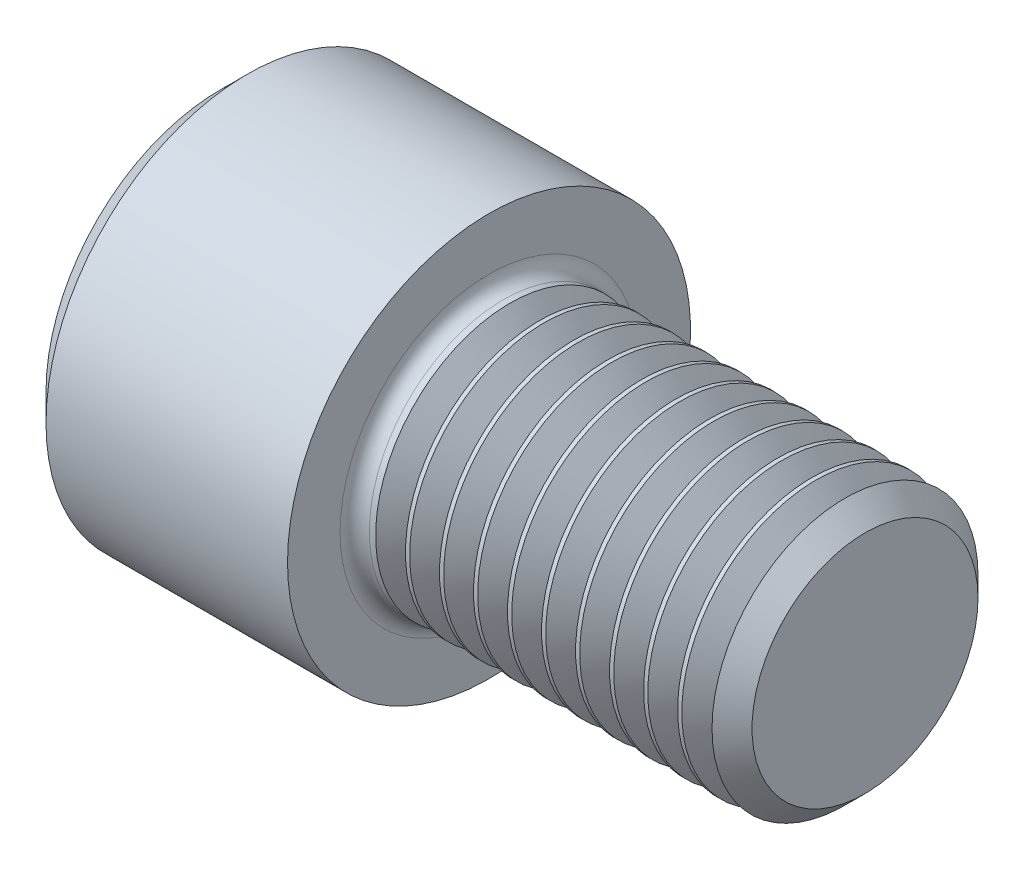
SolidWorks part; units mm, degrees
material "AISI 4130 Steel, normalized at 870C"
ref_plane "Front Plane" through (0, 0, 0) normal (0, 0, 1) x (1, 0, 0)
ref_plane "Top Plane" through (0, 0, 0) normal (0, 1, 0) x (1, 0, 0)
ref_plane "Right Plane" through (0, 0, 0) normal (1, 0, 0) x (0, 0, -1)
ref_plane "Plane1" through (0, 0, 0) normal (0, 0, -1) x (-1, 0, 0)
sketch "Sketch1" plane through (0, 0, 0) normal (0, 0, -1) x (-1, 0, 0)
  line L0 (-7.9375, 5.9538) -> (-7.9375, 0)
  line L1 (-7.9375, 0) -> (0, 0)
  line L2 (0, 0) -> (0, 5.9538)
  line L3 (0, 5.9538) -> (-7.9375, 5.9538)
  line L4 (-7.9375, 0) -> (0, 0) construction
revolve "Revolve1" add sketch "Sketch1" angle 360 about L4
sketch "Sketch2" plane through (7.9375, 0, 0) normal (1, 0, 0) x (0, 0, -1)
  circle A0 centre (0, 0) radius 3.9687
extrude "Boss-Extrude1" add sketch "Sketch2" along normal blind 0.6181
sketch "Sketch3" plane through (8.5556, 0, 0) normal (1, 0, 0) x (0, 0, -1)
  circle A0 centre (0, 0) radius 3.9687
extrude "Boss-Extrude2" add sketch "Sketch3" along normal blind 0.4411 draft 55
sketch "Sketch4" plane through (8.9967, 0, 0) normal (1, 0, 0) x (0, 0, -1)
  circle A0 centre (0, 0) radius 3.3388
extrude "Boss-Extrude3" add sketch "Sketch4" along normal blind 0.4411 draft 55 draft outward yes
sketch "Sketch5" plane through (9.4378, 0, 0) normal (1, 0, 0) x (0, 0, -1)
  circle A0 centre (0, 0) radius 3.9687
extrude "Boss-Extrude4" add sketch "Sketch5" along normal blind 0.1232
sketch "Sketch6" plane through (9.5609, 0, 0) normal (1, 0, 0) x (0, 0, -1)
  circle A0 centre (0, 0) radius 3.9687
extrude "Boss-Extrude5" add sketch "Sketch6" along normal blind 0.4411 draft 55
sketch "Sketch7" plane through (10.002, 0, 0) normal (1, 0, 0) x (0, 0, -1)
  circle A0 centre (0, 0) radius 3.3388
extrude "Boss-Extrude6" add sketch "Sketch7" along normal blind 0.4411 draft 55 draft outward yes
sketch "Sketch8" plane through (10.4431, 0, 0) normal (1, 0, 0) x (0, 0, -1)
  circle A0 centre (0, 0) radius 3.9687
extrude "Boss-Extrude7" add sketch "Sketch8" along normal blind 0.1232
sketch "Sketch9" plane through (10.5663, 0, 0) normal (1, 0, 0) x (0, 0, -1)
  circle A0 centre (0, 0) radius 3.9687
extrude "Boss-Extrude8" add sketch "Sketch9" along normal blind 0.4411 draft 55
sketch "Sketch10" plane through (11.0073, 0, 0) normal (1, 0, 0) x (0, 0, -1)
  circle A0 centre (0, 0) radius 3.3388
extrude "Boss-Extrude9" add sketch "Sketch10" along normal blind 0.4411 draft 55 draft outward yes
sketch "Sketch11" plane through (11.4484, 0, 0) normal (1, 0, 0) x (0, 0, -1)
  circle A0 centre (0, 0) radius 3.9687
extrude "Boss-Extrude10" add sketch "Sketch11" along normal blind 0.1232
sketch "Sketch12" plane through (11.5716, 0, 0) normal (1, 0, 0) x (0, 0, -1)
  circle A0 centre (0, 0) radius 3.9687
extrude "Boss-Extrude11" add sketch "Sketch12" along normal blind 0.4411 draft 55
sketch "Sketch13" plane through (12.0127, 0, 0) normal (1, 0, 0) x (0, 0, -1)
  circle A0 centre (0, 0) radius 3.3388
extrude "Boss-Extrude12" add sketch "Sketch13" along normal blind 0.4411 draft 55 draft outward yes
sketch "Sketch14" plane through (12.4538, 0, 0) normal (1, 0, 0) x (0, 0, -1)
  circle A0 centre (0, 0) radius 3.9687
extrude "Boss-Extrude13" add sketch "Sketch14" along normal blind 0.1232
sketch "Sketch15" plane through (12.5769, 0, 0) normal (1, 0, 0) x (0, 0, -1)
  circle A0 centre (0, 0) radius 3.9688
extrude "Boss-Extrude14" add sketch "Sketch15" along normal blind 0.4411 draft 55
sketch "Sketch16" plane through (13.018, 0, 0) normal (1, 0, 0) x (0, 0, -1)
  circle A0 centre (0, 0) radius 3.3388
extrude "Boss-Extrude15" add sketch "Sketch16" along normal blind 0.4411 draft 55 draft outward yes
sketch "Sketch17" plane through (13.4591, 0, 0) normal (1, 0, 0) x (0, 0, -1)
  circle A0 centre (0, 0) radius 3.9687
extrude "Boss-Extrude16" add sketch "Sketch17" along normal blind 0.1232
sketch "Sketch18" plane through (13.5823, 0, 0) normal (1, 0, 0) x (0, 0, -1)
  circle A0 centre (0, 0) radius 3.9687
extrude "Boss-Extrude17" add sketch "Sketch18" along normal blind 0.4411 draft 55
sketch "Sketch19" plane through (14.0233, 0, 0) normal (1, 0, 0) x (0, 0, -1)
  circle A0 centre (0, 0) radius 3.3388
extrude "Boss-Extrude18" add sketch "Sketch19" along normal blind 0.4411 draft 55 draft outward yes
sketch "Sketch20" plane through (14.4644, 0, 0) normal (1, 0, 0) x (0, 0, -1)
  circle A0 centre (0, 0) radius 3.9687
extrude "Boss-Extrude19" add sketch "Sketch20" along normal blind 0.1232
sketch "Sketch21" plane through (14.5876, 0, 0) normal (1, 0, 0) x (0, 0, -1)
  circle A0 centre (0, 0) radius 3.9688
extrude "Boss-Extrude20" add sketch "Sketch21" along normal blind 0.4411 draft 55
sketch "Sketch22" plane through (15.0287, 0, 0) normal (1, 0, 0) x (0, 0, -1)
  circle A0 centre (0, 0) radius 3.3388
extrude "Boss-Extrude21" add sketch "Sketch22" along normal blind 0.4411 draft 55 draft outward yes
sketch "Sketch23" plane through (15.4697, 0, 0) normal (1, 0, 0) x (0, 0, -1)
  circle A0 centre (0, 0) radius 3.9687
extrude "Boss-Extrude22" add sketch "Sketch23" along normal blind 0.1232
sketch "Sketch24" plane through (15.5929, 0, 0) normal (1, 0, 0) x (0, 0, -1)
  circle A0 centre (0, 0) radius 3.9687
extrude "Boss-Extrude23" add sketch "Sketch24" along normal blind 0.4411 draft 55
sketch "Sketch25" plane through (16.034, 0, 0) normal (1, 0, 0) x (0, 0, -1)
  circle A0 centre (0, 0) radius 3.3388
extrude "Boss-Extrude24" add sketch "Sketch25" along normal blind 0.4411 draft 55 draft outward yes
sketch "Sketch26" plane through (16.4751, 0, 0) normal (1, 0, 0) x (0, 0, -1)
  circle A0 centre (0, 0) radius 3.9687
extrude "Boss-Extrude25" add sketch "Sketch26" along normal blind 0.1232
sketch "Sketch27" plane through (16.5983, 0, 0) normal (1, 0, 0) x (0, 0, -1)
  circle A0 centre (0, 0) radius 3.9687
extrude "Boss-Extrude26" add sketch "Sketch27" along normal blind 0.4411 draft 55
sketch "Sketch28" plane through (17.0393, 0, 0) normal (1, 0, 0) x (0, 0, -1)
  circle A0 centre (0, 0) radius 3.3388
extrude "Boss-Extrude27" add sketch "Sketch28" along normal blind 0.4411 draft 55 draft outward yes
sketch "Sketch29" plane through (17.4804, 0, 0) normal (1, 0, 0) x (0, 0, -1)
  circle A0 centre (0, 0) radius 3.9687
extrude "Boss-Extrude28" add sketch "Sketch29" along normal blind 0.1232
sketch "Sketch30" plane through (17.6036, 0, 0) normal (1, 0, 0) x (0, 0, -1)
  circle A0 centre (0, 0) radius 3.9688
extrude "Boss-Extrude29" add sketch "Sketch30" along normal blind 0.4411 draft 55
sketch "Sketch31" plane through (18.0447, 0, 0) normal (1, 0, 0) x (0, 0, -1)
  circle A0 centre (0, 0) radius 3.3388
extrude "Boss-Extrude30" add sketch "Sketch31" along normal blind 0.414 draft 55 draft outward yes
sketch "Sketch32" plane through (18.4587, 0, 0) normal (1, 0, 0) x (0, 0, -1)
  circle A0 centre (0, 0) radius 3.9301
extrude "Boss-Extrude31" add sketch "Sketch32" along normal blind 0.5913 draft 45
sketch "Sketch33" plane through (0, 0, 0) normal (-1, 0, 0) x (0, 0, 1)
  line L0 (-3.175, -1.8331) -> (0, -3.6662)
  line L1 (0, -3.6662) -> (3.175, -1.8331)
  line L2 (3.175, -1.8331) -> (3.175, 1.8331)
  line L3 (3.175, 1.8331) -> (0, 3.6662)
  line L4 (0, 3.6662) -> (-3.175, 1.8331)
  line L5 (-3.175, 1.8331) -> (-3.175, -1.8331)
extrude "Cut-Extrude1" cut sketch "Sketch33" against normal blind 3.8354
sketch "Sketch34" plane through (0, 0, 0) normal (0, 0, 1) x (1, 0, 0)
  line L0 (3.8354, 3.175) -> (3.8354, 0)
  line L1 (3.8354, 0) -> (5.6685, 0)
  line L2 (5.6685, 0) -> (3.8354, 3.175)
  line L3 (3.8354, 0) -> (5.6686, 0) construction
revolve "Cut-Revolve1" cut sketch "Sketch34" angle 360 about L3
chamfer "Chamfer1" distance 0.8001 angle 45 1 edges at (0, 0, 5.9538)
fillet "Fillet1" radius 0.4318 1 edges at (7.9375, 0, -3.9687)
